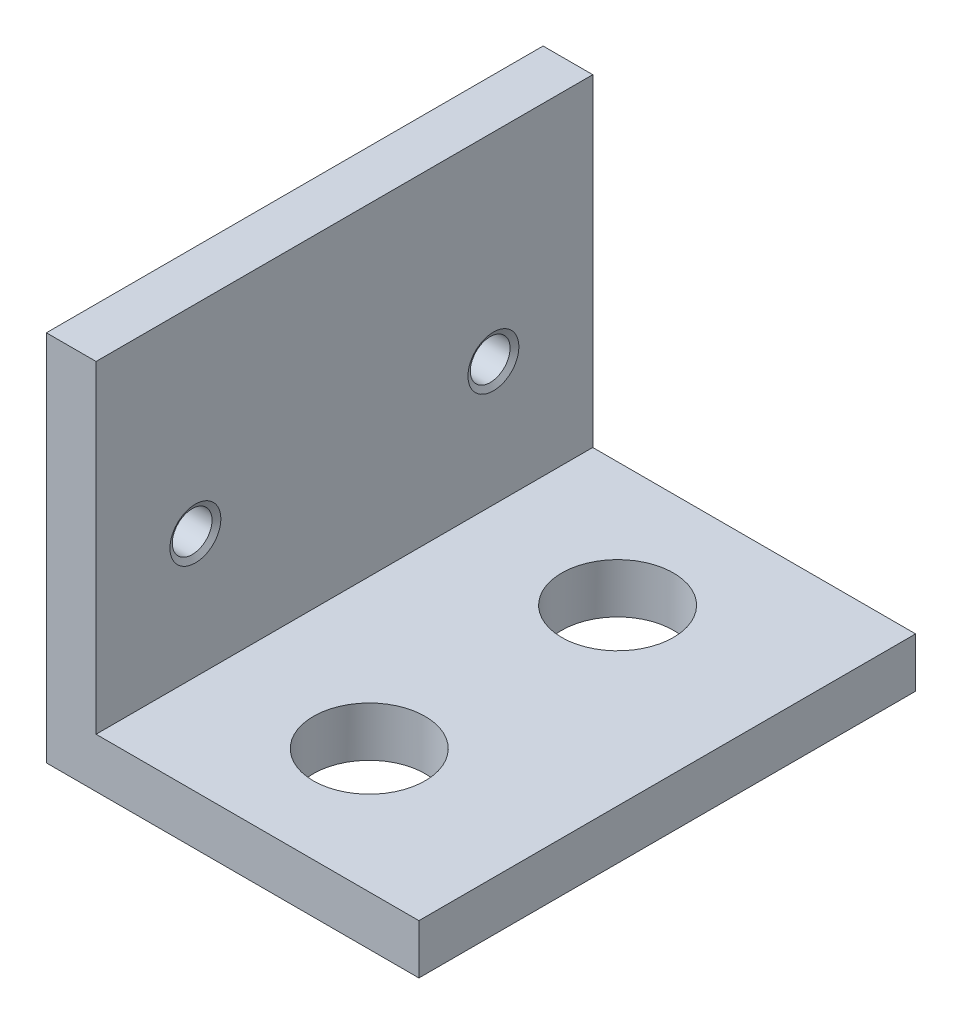
SolidWorks part; units mm, degrees
material "Д16Т ГОСТ 4784-74"
ref_plane "Спереди" through (0, 0, 0) normal (0, 0, 1) x (1, 0, 0)
ref_plane "Сверху" through (0, 0, 0) normal (0, 1, 0) x (1, 0, 0)
ref_plane "Справа" through (0, 0, 0) normal (1, 0, 0) x (0, 0, -1)
sketch "Эскиз1" plane through (0, 0, 0) normal (0, 0, 1) x (1, 0, 0)
  line L0 (0, 0) -> (0, 15)
  line L1 (0, 15) -> (2, 15)
  line L2 (2, 15) -> (2, 2)
  line L3 (2, 2) -> (15, 2)
  line L4 (15, 2) -> (15, 0)
  line L5 (15, 0) -> (0, 0)
  dimension "D1" = 2
  dimension "D2" = 15
extrude "Бобышка-Вытянуть1" add sketch "Эскиз1" along normal blind 20
hole_wizard "Отверстие с зазором M41" positions "Эскиз3" profile "Эскиз2" hole size "M4" standard "DIN"
sketch "Эскиз3" plane through (0, 2, 0) normal (0, 1, 0) x (-1, 0, 0)
  line L0 (-15, 20) -> (-15, 0) construction
  line L1 (-15, 0) -> (-2, 0) construction
  line L2 (-15, 20) -> (-2, 20) construction
  point P0 (-8, 5)
  point P1 (-8, 15)
  dimension "D1" = 7
  dimension "D2" = 5
  dimension "D3" = 5
sketch "Эскиз2" plane through (8, 2, 5) normal (1, 0, 0) x (0, 0, 1)
  line L0 (0, 0) -> (0, 6.3519)
  line L1 (0, 6.3519) -> (2.25, 5)
  line L2 (2.25, 5) -> (2.25, 0)
  line L5 (2.25, 0) -> (0, 0)
  line L10 (0, 6.3519) -> (-2.25, 5) construction
  line L11 (0, -6.35) -> (0, 107.95) construction
  dimension "Диаметр отверстия" = 4.5
  dimension "Глубина отверстия" = 5
  dimension "Угол заточки сверла" = 118
hole_wizard "Отверстие обработанное метчиком M21" positions "Эскиз5" profile "Эскиз4" tap size "M2" standard "DIN"
sketch "Эскиз5" plane through (2, 0, 0) normal (1, 0, 0) x (0, 0, -1)
  line L0 (0, 2) -> (0, 15) construction
  line L1 (-20, 15) -> (0, 15) construction
  line L2 (-20, 2) -> (-20, 15) construction
  point P0 (-4, 7)
  point P5 (-16, 7)
  dimension "D1" = 4
  dimension "D2" = 8
  dimension "D3" = 4
sketch "Эскиз4" plane through (2, 7, 4) normal (0, 1, 0) x (0, 0, -1)
  line L0 (0, 0) -> (0, 6.4807)
  line L1 (0, 6.4807) -> (0.8, 6)
  line L2 (0.8, 6) -> (0.8, 0.1299)
  line L3 (0.8, 0.1299) -> (1.025, 0)
  line L5 (1.025, 0) -> (0, 0)
  line L6 (-0.8, 0.1299) -> (-1.025, 0) construction
  line L10 (0, 6.4807) -> (-0.8, 6) construction
  line L11 (0, -6.35) -> (0, 107.95) construction
  dimension "Диаметр сверла" = 1.6
  dimension "Глубина сверла" = 6
  dimension "Диаметр передней зенковки" = 2.05
  dimension "Угол передней зенковки" = 120
  dimension "Угол заточки сверла" = 118
cosmetic thread "Отверстие резьбы1" parameters "D1"=2, "D2"=2
cosmetic thread "Отверстие резьбы2" parameters "D1"=2, "D2"=2
